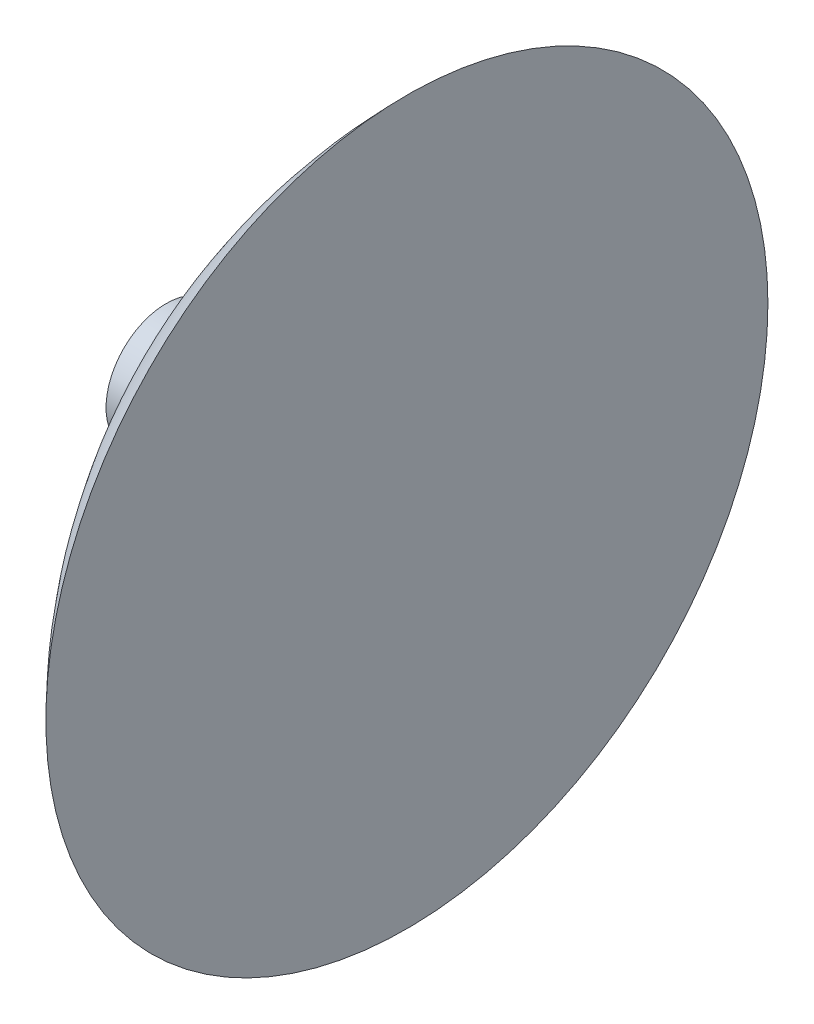
SolidWorks part; units mm, degrees
ref_plane "Front Plane" through (0, 0, 0) normal (0, 0, 1) x (1, 0, 0)
ref_plane "Top Plane" through (0, 0, 0) normal (0, 1, 0) x (1, 0, 0)
ref_plane "Right Plane" through (0, 0, 0) normal (1, 0, 0) x (0, 0, -1)
sketch "Sketch1" plane through (0, 0, 0) normal (0, 1, 0) x (1, 0, 0)
  line L1 (-750, 750) -> (-750, 0)
  line L2 (-1060.6602, 0) -> (-750, 0)
  line L3 (-1110.594, 0) -> (252.9585, 0) construction
  arc A0 (-750, 750) -> (-1060.6602, 0) centre (0, 0) ccw
  dimension "D1" = 750
revolve "Revolve1" add sketch "Sketch1" angle 360 about L3
sketch "Sketch2" plane through (-750, 0, 0) normal (1, 0, 0) x (0, 0, -1)
  circle A0 centre (0, 0) radius 125
  dimension "D1" = 250
extrude "Boss-Extrude1" add sketch "Sketch2" against normal blind 500
sketch "Sketch3" plane through (-1250, 0, 0) normal (-1, 0, 0) x (0, 0, 1)
  point P0 (0, 0)
